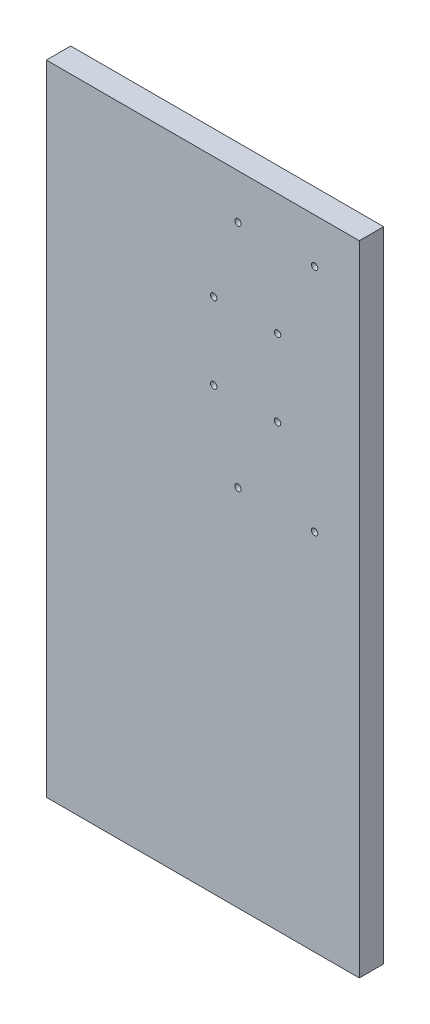
SolidWorks part; units mm, degrees
ref_plane "Front Plane" through (0, 0, 0) normal (0, 0, 1) x (1, 0, 0)
ref_plane "Top Plane" through (0, 0, 0) normal (0, 1, 0) x (1, 0, 0)
ref_plane "Right Plane" through (0, 0, 0) normal (1, 0, 0) x (0, 0, -1)
sketch "Sketch1" plane through (0, 0, 0) normal (0, 0, 1) x (1, 0, 0)
  line L1 (-245.05, 250) -> (0, 250)
  line L2 (-245.05, 250) -> (-245.05, -250)
  line L3 (-245.05, -250) -> (0, -250)
  line L4 (0, 250) -> (0, -250)
  dimension "D1" = 500
  dimension "D2" = 245.05
extrude "Boss-Extrude1" add sketch "Sketch1" along normal blind 19.05
hole_wizard "Ø5.0mm Dowel Hole1" positions "Sketch2" profile "Sketch3" hole size "Ø5.0" standard "ANSI Metric"
sketch "Sketch2" plane through (0, 0, 0) normal (0, 0, -1) x (-1, 0, 0)
  point P0 (35, 35)
  point P6 (95, 35)
  point P15 (114, 95)
  point P18 (64, 95)
  point P21 (64, 155)
  point P24 (35, 215)
  point P30 (95, 215)
  point P39 (114, 155)
sketch "Sketch3" plane through (-35, 35, 0) normal (1, 0, 0) x (0, 1, 0)
  line L0 (0, 0) -> (0, 30)
  line L1 (0, 30) -> (2.5, 28.4978)
  line L2 (2.5, 28.4978) -> (2.5, 0)
  line L5 (2.5, 0) -> (0, 0)
  line L10 (0, 30) -> (-2.5, 28.4978) construction
  line L11 (0, -6.35) -> (0, 107.95) construction
  dimension "Hole Dia." = 5
  dimension "Hole Depth" = 30
  dimension "Drill Angle" = 118
